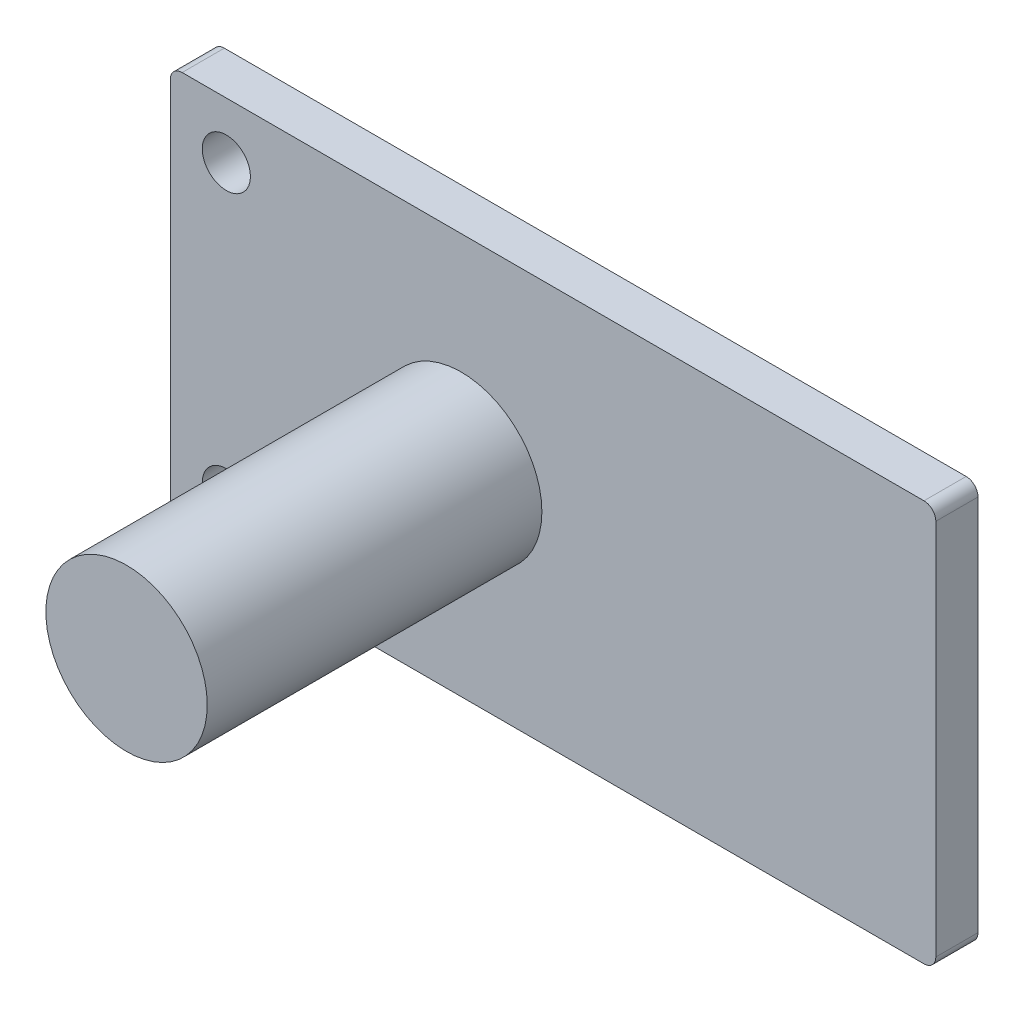
SolidWorks part; units mm, degrees
ref_plane "前视基准面" through (0, 0, 0) normal (0, 0, 1) x (1, 0, 0)
ref_plane "上视基准面" through (0, 0, 0) normal (0, 1, 0) x (1, 0, 0)
ref_plane "右视基准面" through (0, 0, 0) normal (1, 0, 0) x (0, 0, -1)
other "Configuration Table"
sketch "草图1" plane through (0, 0, 0) normal (0, 0, 1) x (1, 0, 0)
  line L0 (0.5, 0) -> (31.8, 0)
  line L1 (32.3, 0.5) -> (32.3, 16.42)
  line L2 (31.8, 16.92) -> (0.5, 16.92)
  line L3 (0, 16.42) -> (0, 0.5)
  arc A0 (31.8, 0) -> (32.3, 0.5) centre (31.8, 0.5) ccw
  arc A1 (32.3, 16.42) -> (31.8, 16.92) centre (31.8, 16.42) ccw
  arc A2 (0.5, 16.92) -> (0, 16.42) centre (0.5, 16.42) ccw
  arc A3 (0, 0.5) -> (0.5, 0) centre (0.5, 0.5) ccw
extrude "Measured_encoder_PCB" add sketch "草图1" along normal blind 1.78
sketch "草图2" plane through (0, 0, 0) normal (0, 0, 1) x (1, 0, 0)
  circle A0 centre (2.365, 2.365) radius 1.015
  circle A1 centre (2.365, 14.555) radius 1.015
extrude "Measured_encoder_mount_holes" cut sketch "草图2" along normal blind 2
sketch "草图3" plane through (0, 0, 0) normal (0, 0, 1) x (1, 0, 0)
  circle A0 centre (12.275, 8.46) radius 3.405
extrude "Shaft_clearance_reference" add sketch "草图3" along normal blind 14.12 from offset 1.78
